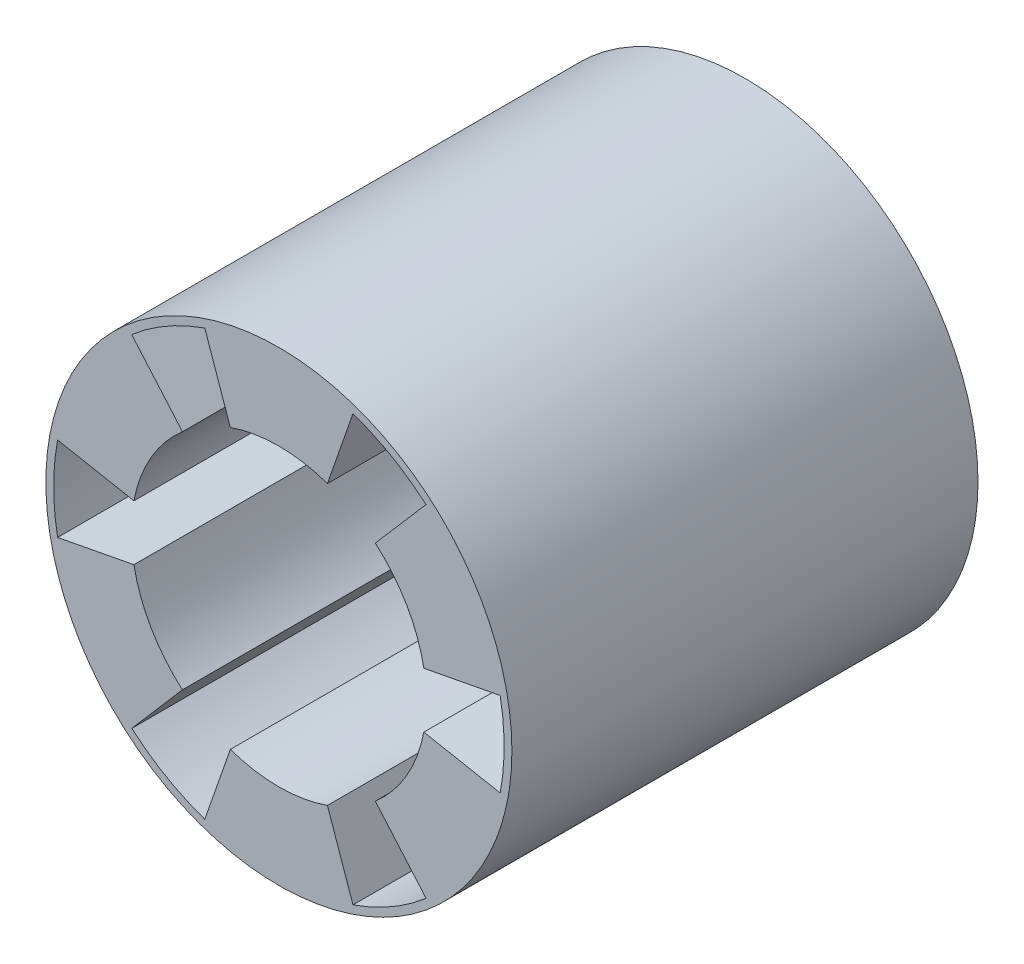
SolidWorks part; units mm, degrees
ref_plane "Front Plane" through (0, 0, 0) normal (0, 0, 1) x (1, 0, 0)
ref_plane "Top Plane" through (0, 0, 0) normal (0, 1, 0) x (1, 0, 0)
ref_plane "Right Plane" through (0, 0, 0) normal (1, 0, 0) x (0, 0, -1)
sketch "Sketch4" plane through (0, 0, 0) normal (0, 0, 1) x (1, 0, 0)
  circle A0 centre (0, 0) radius 30
  dimension "D1" = 60
extrude "Boss-Extrude2" add sketch "Sketch4" along normal blind 60
sketch "Sketch5" plane through (0, 0, 0) normal (0, 0, -1) x (-1, 0, 0)
  line L0 (0, 0) -> (0, 32.5287) construction
  line L1 (-6.2493, 17.9429) -> (-9.5383, 27.3865)
  line L2 (6.2493, 17.9429) -> (9.5383, 27.3865)
  line L3 (12.4144, 14.3835) -> (18.9482, 21.9537)
  line L4 (18.6636, 3.5594) -> (28.4866, 5.4328)
  line L5 (18.6636, -3.5594) -> (28.4866, -5.4328)
  line L6 (12.4144, -14.3835) -> (18.9482, -21.9537)
  line L7 (6.2493, -17.9429) -> (9.5383, -27.3865)
  line L8 (-6.2493, -17.9429) -> (-9.5383, -27.3865)
  line L9 (-12.4144, -14.3835) -> (-18.9482, -21.9537)
  line L10 (-18.6636, -3.5594) -> (-28.4866, -5.4328)
  line L11 (-18.6636, 3.5594) -> (-28.4866, 5.4328)
  line L12 (-12.4144, 14.3835) -> (-18.9482, 21.9537)
  arc A0 (-28.4866, 5.4328) -> (-28.4866, -5.4328) centre (0, 0) ccw
  arc A1 (-9.5383, 27.3865) -> (-18.9482, 21.9537) centre (0, 0) ccw
  arc A2 (-12.4144, 14.3835) -> (-18.6636, 3.5594) centre (0, 0) ccw
  arc A3 (6.2493, 17.9429) -> (-6.2493, 17.9429) centre (0, 0) ccw
  arc A4 (18.6636, 3.5594) -> (12.4144, 14.3835) centre (0, 0) ccw
  arc A5 (12.4144, -14.3835) -> (18.6636, -3.5594) centre (0, 0) ccw
  arc A6 (-6.2493, -17.9429) -> (6.2493, -17.9429) centre (0, 0) ccw
  arc A7 (-18.6636, -3.5594) -> (-12.4144, -14.3835) centre (0, 0) ccw
  arc A8 (18.9482, 21.9537) -> (9.5383, 27.3865) centre (0, 0) ccw
  arc A9 (28.4866, -5.4328) -> (28.4866, 5.4328) centre (0, 0) ccw
  arc A10 (9.5383, -27.3865) -> (18.9482, -21.9537) centre (0, 0) ccw
  arc A11 (-18.9482, -21.9537) -> (-9.5383, -27.3865) centre (0, 0) ccw
  point P32 (0, 0)
  dimension "D1" = 58
  dimension "D2" = 38
  dimension "D3" = 6
extrude "Cut-Extrude1" cut sketch "Sketch5" against normal through all contours L11 A0 L10 A7 L9 A11 L8 A6 L7 A10 L6 A5 L5 A9 L4 A4 L3 A8 L2 A3 L1 A1 L12 A2
sketch "Sketch8" plane through (0, 0, 0) normal (0, 0, 1) x (1, 0, 0)
  line L0 (0, 0) -> (-13.5673, 15.7192) construction
  line L1 (-12.4144, 14.3835) -> (-18.9482, 21.9537) construction
  line L2 (0, 0) -> (-20.0294, 3.8199) construction
  line L3 (-18.6636, 3.5594) -> (-28.4866, 5.4328) construction
  dimension "D1" = 38.405
